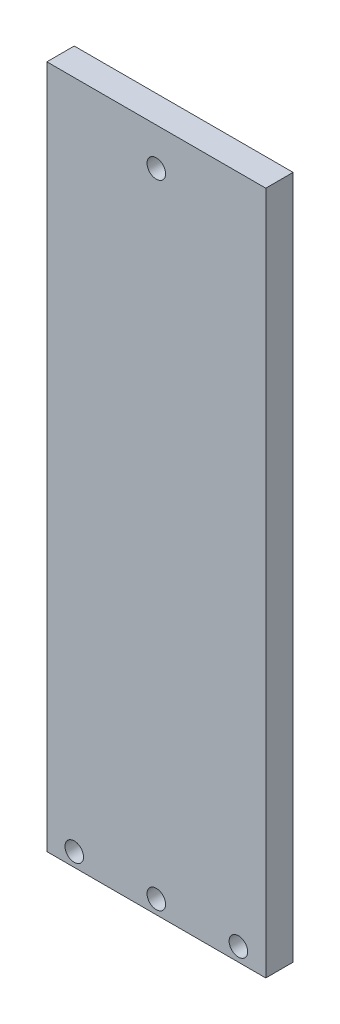
SolidWorks part; units mm, degrees
ref_plane "Front Plane" through (0, 0, 0) normal (0, 0, 1) x (1, 0, 0)
ref_plane "Top Plane" through (0, 0, 0) normal (0, 1, 0) x (1, 0, 0)
ref_plane "Right Plane" through (0, 0, 0) normal (1, 0, 0) x (0, 0, -1)
sketch "Sketch1" plane through (0, 0, 0) normal (0, 0, 1) x (1, 0, 0)
  line L0 (-25.4, -76.2) -> (-25.4, -82.55)
  line L1 (-25.4, -76.2) -> (25.4, -76.2) construction
  line L2 (-25.4, -76.2) -> (-25.4, 76.2)
  line L3 (-25.4, 76.2) -> (25.4, 76.2)
  line L4 (25.4, -76.2) -> (25.4, 76.2)
  line L5 (-25.4, -76.2) -> (25.4, 76.2) construction
  line L6 (-25.4, 76.2) -> (25.4, -76.2) construction
  line L7 (-25.4, -82.55) -> (25.4, -82.55)
  line L8 (25.4, -82.55) -> (25.4, -76.2)
  circle A0 centre (0, 67.4497) radius 2.1527
  circle A1 centre (-19.05, -79.375) radius 2.1527
  circle A2 centre (0, -79.375) radius 2.1527
  circle A3 centre (19.05, -79.375) radius 2.1527
  point P0 (0, 0)
  dimension "D3" = 4.3053
  dimension "D6" = 4.3053
  dimension "D1" = 50.8
  dimension "D2" = 152.4
  dimension "D4" = 143.6497
  dimension "D5" = 6.35
  dimension "D7" = 6.35
  dimension "D8" = 3.175
extrude "Boss-Extrude1" add sketch "Sketch1" along normal mid plane 6.35
